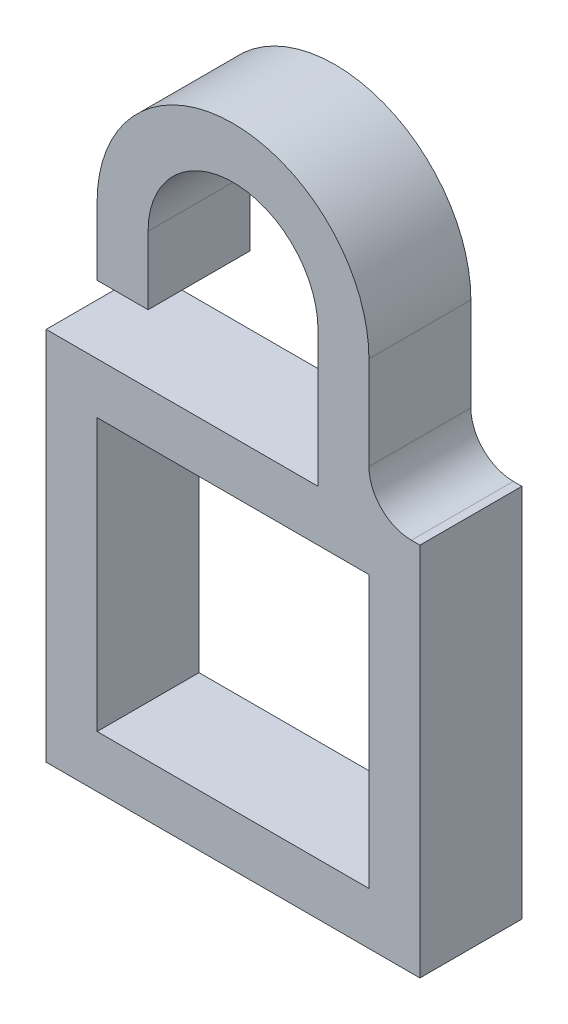
SolidWorks part; units mm, degrees
ref_plane "前视基准面" through (0, 0, 0) normal (0, 0, 1) x (1, 0, 0)
ref_plane "上视基准面" through (0, 0, 0) normal (0, 1, 0) x (1, 0, 0)
ref_plane "右视基准面" through (0, 0, 0) normal (1, 0, 0) x (0, 0, -1)
sketch "草图1" plane through (0, 0, 0) normal (0, 0, 1) x (1, 0, 0)
  line L0 (0, -16) -> (0, 0) construction
  line L1 (-10, -8) -> (-10, 0)
  line L2 (10, -16) -> (10, 0)
  line L4 (-10, -16) -> (10, -16)
  line L5 (-10, -22) -> (10, -22)
  line L7 (-16, -8) -> (-16, 0)
  line L8 (16, -16) -> (16, 0)
  line L9 (-16, -8) -> (-10, -8)
  line L10 (16, -16) -> (-16, -16)
  line L11 (16, -22) -> (10, -22)
  line L12 (-16, -22) -> (-10, -22)
  line L13 (-16, -22) -> (-16, -54)
  line L14 (-16, -54) -> (-22, -54)
  line L15 (-22, -54) -> (-22, -16)
  line L16 (-22, -16) -> (-16, -16)
  line L17 (22, -16) -> (16, -16)
  line L18 (22, -54) -> (22, -16)
  line L19 (16, -54) -> (22, -54)
  line L20 (16, -22) -> (16, -54)
  line L21 (-22, -54) -> (-22, -60.1298)
  line L22 (-22, -60.1298) -> (22, -60.1298)
  line L23 (22, -60.1298) -> (22, -54)
  line L24 (16, -54) -> (-16, -54)
  arc A1 (10, 0) -> (-10, 0) centre (0, 0) ccw
  arc A2 (16, 0) -> (-16, 0) centre (0, 0) ccw
  point P3 (0, -10)
  dimension "D1" = 8
  dimension "D2" = 6
  dimension "D4" = 16
  dimension "D3" = 20
  dimension "D5" = 32
  dimension "D6" = 6
  dimension "D7" = 32
  dimension "D8" = 38
extrude "凸台-拉伸1" add sketch "草图1" along normal blind 12 contours L8 A2 L7 L9 L1 A1 L2 L10 | L11 L20 L19 L18 L17 L10 L4 L16 L15 L14 L13 L12 L5 | L19 L24 L14 L21 L22 L23
fillet "圆角1" radius 5 1 edges at (16, -16, 6)
